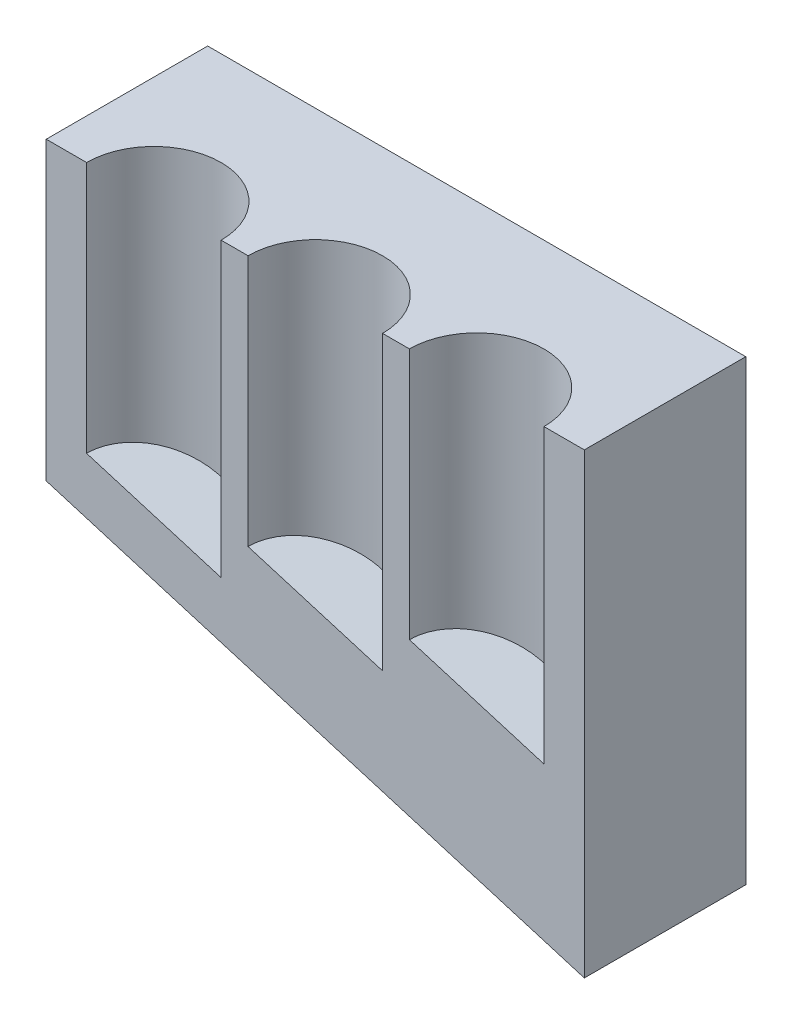
SolidWorks part; units mm, degrees
ref_plane "Front Plane" through (0, 0, 0) normal (0, 0, 1) x (1, 0, 0)
ref_plane "Top Plane" through (0, 0, 0) normal (0, 1, 0) x (1, 0, 0)
ref_plane "Right Plane" through (0, 0, 0) normal (1, 0, 0) x (0, 0, -1)
sketch "Sketch1" plane through (0, 0, 0) normal (0, 0, 1) x (1, 0, 0)
  line L1 (0, 0) -> (100, -30)
  line L2 (0, 0) -> (0, 55)
  line L3 (0, 55) -> (100, 55)
  line L4 (100, -30) -> (100, 55)
  dimension "D1" = 100
  dimension "D2" = 85
  dimension "D3" = 55
extrude "Extrude1" add sketch "Sketch1" along normal blind 30
sketch "Sketch2" plane through (0, 55, 0) normal (0, 1, 0) x (1, 0, 0)
  line L0 (100, -30) -> (0, -30) construction
  line L1 (0, -30) -> (0, 0) construction
  circle A0 centre (20, -30) radius 12.5
  dimension "D1" = 25
  dimension "D2" = 20
extrude "Extrude2" cut sketch "Sketch2" against normal offset from surface (68.5597 mm away) 10
pattern_linear "LPattern1" count 3 spacing 30 along (1, 0, 0) of "Extrude2"
